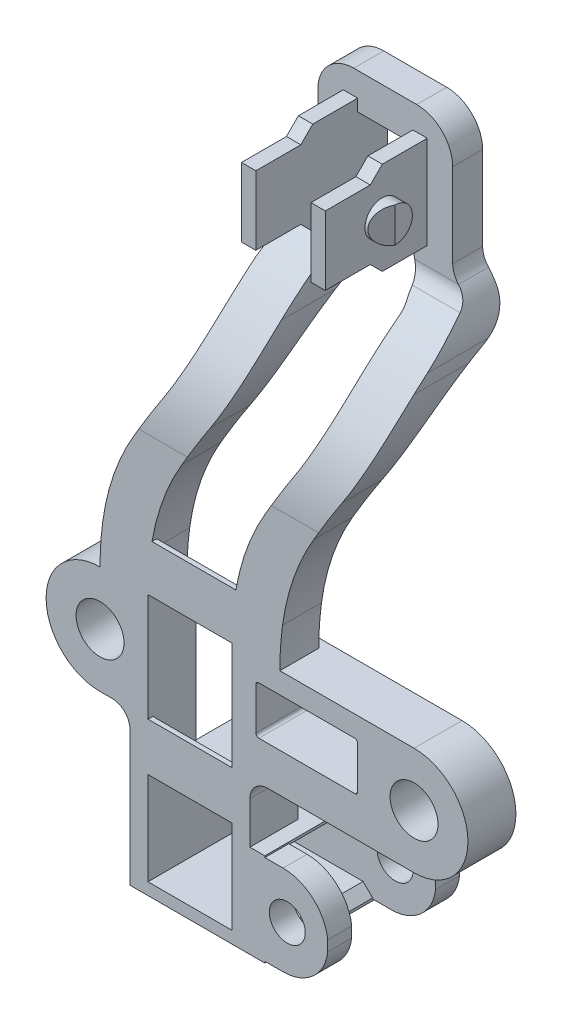
SolidWorks part; units mm, degrees
material "PET"
ref_plane "Front Plane" through (0, 0, 0) normal (0, 0, 1) x (1, 0, 0)
ref_plane "Top Plane" through (0, 0, 0) normal (0, 1, 0) x (1, 0, 0)
ref_plane "Right Plane" through (0, 0, 0) normal (1, 0, 0) x (0, 0, -1)
sketch "Sketch1" plane through (0, 0, 0) normal (0, 0, 1) x (1, 0, 0)
  line L0 (42.5, -2.5) -> (26.5, -2.5)
  line L1 (43, -2) -> (43, 5)
  line L2 (42.5, 5.5) -> (26.5, 5.5)
  line L3 (26, -2) -> (26, 5)
  line L84 (38, -34.5) -> (38, -19)
  line L94 (19.35, 79.25) -> (19.35, 65.25)
  line L96 (41.85, 79.25) -> (41.85, 65.25)
  line L97 (25.35, 85.25) -> (35.85, 85.25)
  line L112 (30, 9) -> (52.4, 9)
  line L113 (39.9183, 37.9809) -> (35.6739, 30.809)
  line L114 (31.9183, 37.7984) -> (27.6739, 30.6266)
  line L115 (17.9183, 37.7984) -> (13.6739, 30.6266)
  line L116 (9.9183, 37.9809) -> (5.6739, 30.809)
  line L121 (22, -19) -> (8, -19)
  line L122 (8, -19) -> (8, 8.8176)
  line L123 (22, -19) -> (22, 8.8176)
  line L126 (52.4, -9) -> (28, -9)
  line L127 (25, -12) -> (25, -19)
  line L128 (25, -19) -> (38, -19)
  line L129 (0, -9) -> (2, -9)
  line L130 (5, -12) -> (5, -34.5)
  line L131 (5, -34.5) -> (38, -34.5)
  line L134 (26, 65.25) -> (26, 79.25)
  line L135 (26, 79.25) -> (35.2, 79.25)
  line L136 (35.2, 65.25) -> (35.2, 79.25)
  circle A66 centre (0, 0) radius 4
  circle A67 centre (52.4, 0) radius 4
  arc A68 (43, 5) -> (42.5, 5.5) centre (42.5, 5) ccw
  arc A69 (42.5, -2.5) -> (43, -2) centre (42.5, -2) ccw
  arc A70 (26.5, -2.5) -> (26, -2) centre (26.5, -2) cw
  arc A71 (26.5, 5.5) -> (26, 5) centre (26.5, 5) ccw
  arc A73 (52.4, -9) -> (52.4, 9) centre (52.4, 0) ccw
  arc A122 (25.35, 85.25) -> (19.35, 79.25) centre (25.35, 79.25) ccw
  arc A123 (41.85, 79.25) -> (35.85, 85.25) centre (35.85, 79.25) ccw
  arc A134 (0, 9) -> (0, -9) centre (0, 0) ccw
  arc A142 (30.4608, 15.8181) -> (30, 9) centre (80.6766, 9) ccw
  arc A146 (30.4608, 15.8181) -> (35.6739, 30.809) centre (70.0971, 10.4364) cw
  arc A147 (45.1088, 52.8075) -> (39.9183, 37.9809) centre (5.4951, 58.3534) cw
  arc A148 (22.4608, 15.6357) -> (22, 8.8176) centre (72.6766, 8.8176) ccw
  arc A149 (37.1088, 52.6251) -> (37.5686, 57.8889) centre (-13.259, 59.6766) ccw
  arc A150 (22.4608, 15.6357) -> (27.6739, 30.6266) centre (62.0971, 10.254) cw
  arc A151 (37.1088, 52.6251) -> (31.9183, 37.7984) centre (-2.5049, 58.171) cw
  arc A152 (8.4608, 15.6357) -> (8, 8.8176) centre (58.6766, 8.8176) ccw
  arc A153 (23.1088, 52.6251) -> (23.5705, 57.9444) centre (-27.259, 59.6766) ccw
  arc A154 (8.4608, 15.6357) -> (13.6739, 30.6266) centre (48.0971, 10.254) cw
  arc A155 (23.1088, 52.6251) -> (17.9183, 37.7984) centre (-16.5049, 58.171) cw
  arc A156 (0.4608, 15.8181) -> (0, 9) centre (50.6766, 9) ccw
  arc A158 (0.4608, 15.8181) -> (5.6739, 30.809) centre (40.0971, 10.4364) cw
  arc A159 (15.1088, 52.8075) -> (9.9183, 37.9809) centre (-24.5049, 58.3534) cw
  arc A160 (15.1088, 52.8075) -> (15.4789, 56.3512) centre (-35.259, 59.859) ccw
  arc A161 (18.2877, 62.6349) -> (19.35, 65.25) centre (15.6, 65.25) ccw
  arc A162 (45.1088, 52.8075) -> (45.3737, 55.0669) centre (-5.259, 59.859) ccw
  arc A163 (41.85, 65.25) -> (42.8232, 62.7298) centre (45.6, 65.25) ccw
  arc A164 (45.3737, 55.0669) -> (42.8232, 62.7298) centre (35.4182, 56.0091) ccw
  arc A165 (18.2877, 62.6349) -> (15.4789, 56.3512) centre (25.4551, 55.6615) ccw
  arc A169 (35.2, 65.25) -> (37.1876, 59.1352) centre (45.6, 65.25) ccw
  arc A170 (23.9614, 59.0655) -> (26, 65.25) centre (15.6, 65.25) ccw
  arc A171 (37.1876, 59.1352) -> (37.5686, 57.8889) centre (35.5698, 57.9592) cw
  arc A172 (23.9614, 59.0655) -> (23.5705, 57.9444) centre (25.5693, 57.8762) ccw
  arc A173 (2, -9) -> (5, -12) centre (2, -12) cw
  arc A174 (28, -9) -> (25, -12) centre (28, -12) ccw
extrude "Boss-Extrude1" add sketch "Sketch1" along normal blind 22
sketch "Sketch4" plane through (41.85, 0, 0) normal (1, 0, 0) x (0, 0, -1)
  line L1 (-22, 81.25) -> (-5, 81.25)
  line L2 (-22, 81.25) -> (-22, 65.75)
  line L3 (-22, 65.75) -> (-5, 65.75)
  line L4 (-5, 81.25) -> (-5, 65.75)
  circle A0 centre (-12.5, 73.5) radius 2.9
sketch "Sketch5" plane through (19.35, 0, 0) normal (-1, 0, 0) x (0, 0, 1)
  line L3 (5, 81.25) -> (5, 65.75)
  line L4 (22, 65.75) -> (5, 65.75)
  line L5 (22, 81.25) -> (22, 65.75)
  line L6 (22, 81.25) -> (5, 81.25)
  circle A1 centre (12.5, 73.5) radius 2.9
extrude "Cut-Extrude2" cut sketch "Sketch5" against normal offset from surface (4.25 mm away) 2.4 up to face at (26, 72.25, 11)
extrude "Cut-Extrude3" cut sketch "Sketch4" against normal offset from surface (4.25 mm away) 2.4 up to face at (35.2, 72.25, 11)
sketch "Sketch6" plane through (23.6, 0, 0) normal (-1, 0, 0) x (0, 0, 1)
  line L7 (12.5, 81.25) -> (14.5, 79.25)
  line L8 (14.5, 79.25) -> (22, 79.25)
  line L10 (12.5, 65.75) -> (14.5, 67.75)
  line L11 (14.5, 67.75) -> (22, 67.75)
  line L12 (12.5, 81.25) -> (22, 81.25)
  line L13 (22, 81.25) -> (22, 79.25)
  line L14 (12.5, 65.75) -> (22, 65.75)
  line L15 (22, 65.75) -> (22, 67.75)
extrude "Cut-Extrude4" cut sketch "Sketch6" against normal up to surface (14 mm away)
sketch "Sketch7" plane through (0, 0, 22) normal (0, 0, 1) x (1, 0, 0)
  line L5 (19.35, 65.75) -> (19.35, 65.25)
  line L7 (19.35, 65.25) -> (41.85, 65.25)
  line L8 (19.35, 85.25) -> (41.85, 85.25)
  line L9 (41.85, 65.25) -> (41.85, 65.75)
  line L11 (19.35, 85.25) -> (19.35, 81.25)
  line L16 (41.85, 85.25) -> (41.85, 81.25)
  line L19 (26, 65.75) -> (26, 81.25)
  line L21 (35.2, 65.75) -> (35.2, 81.25)
  line L22 (19.35, 65.75) -> (26, 65.75)
  line L23 (41.85, 65.75) -> (35.2, 65.75)
  line L24 (19.35, 81.25) -> (26, 81.25)
  line L25 (41.85, 81.25) -> (35.2, 81.25)
extrude "Cut-Extrude5" cut sketch "Sketch7" against normal up to surface (17 mm away) up to face at (40.0984, 74.6529, 5)
sketch "Sketch8" plane through (0, 81.25, 0) normal (0, 1, 0) x (1, 0, 0)
  line L0 (21.5, -12.5) -> (23.1, -15.4)
  line L3 (21.475, -9.6) -> (21.5, -12.5)
  line L4 (37.6, -15.4) -> (41.85, -15.4) construction
  line L6 (23.6, -9.6) -> (19.35, -9.6) construction
  line L15 (39.7, -12.5) -> (38.1, -15.4)
  line L16 (19.35, -9.6) -> (21.475, -9.6)
  line L17 (19.35, -9.6) -> (19.35, -15.4)
  line L18 (19.35, -15.4) -> (23.1, -15.4)
  line L19 (39.725, -9.6) -> (39.7, -12.5)
  line L20 (41.85, -9.6) -> (37.6, -9.6) construction
  line L21 (41.85, -9.6) -> (39.725, -9.6)
  line L24 (38.1, -15.4) -> (41.85, -15.4)
  line L25 (41.85, -15.4) -> (41.85, -9.6)
extrude "Cut-Extrude6" cut sketch "Sketch8" against normal up to surface (15.5 mm away) up to face at (36.4, 65.75, 8.75)
sketch "Sketch12" plane through (0, 0, 0) normal (1, 0, 0) x (0, 0, -1)
  line L2 (-22, 65.25) -> (-5, 65.25)
  line L4 (-15.5, 9) -> (0, 9)
  line L7 (-5, 65.25) -> (-5, 62.7396)
  line L9 (-15.5, 32.1618) -> (-15.5, 9)
  line L11 (-22, 65.25) -> (-22, 32.1618)
  line L12 (0, 9) -> (0, 60.9585)
  arc A4 (-3.5942, 54.281) -> (-15.5, 32.1618) centre (11, 32.1618) ccw
  arc A5 (-6.4167, 60.1914) -> (-22, 32.1618) centre (11, 32.1618) ccw
  arc A6 (-6.4167, 60.1914) -> (-5, 62.7396) centre (-8, 62.7396) ccw
  arc A7 (-3.5942, 54.281) -> (0, 60.9585) centre (-8, 60.9585) ccw
extrude "Cut-Extrude7" cut sketch "Sketch12" against normal through all both and the other way through all
sketch "Sketch13" plane through (0, 0, 0) normal (1, 0, 0) x (0, 0, -1)
  line L2 (-14, 9) -> (0, 9)
  line L10 (0, 9) -> (0, -19)
  line L11 (-14, -19) -> (0, -19)
  line L12 (-14, 9) -> (-14, -19)
extrude "Cut-Extrude8" cut sketch "Sketch13" against normal through all both and the other way through all
sketch "Sketch14" plane through (38, 0, 0) normal (1, 0, 0) x (0, 0, -1)
  line L0 (-18, -21) -> (-4, -21)
  line L1 (-18, -21) -> (-18, -32.5)
  line L2 (-18, -32.5) -> (-4, -32.5)
  line L3 (-4, -21) -> (-4, -32.5)
extrude "Cut-Extrude9" cut sketch "Sketch14" against normal up to surface (30 mm away) up to face at (8, -5.0912, 18)
sketch "Sketch15" plane through (0, 0, 22) normal (0, 0, 1) x (1, 0, 0)
  line L3 (8, -32.5) -> (22, -32.5)
  line L4 (8, -32.5) -> (8, -19)
  line L5 (8, -19) -> (22, -19)
  line L6 (22, -32.5) -> (22, -19)
extrude "Cut-Extrude10" cut sketch "Sketch15" against normal up to surface (8 mm away) up to face at (34.5, 1.5, 14)
sketch "Sketch16" plane through (0, 0, 0) normal (0, 0, -1) x (-1, 0, 0)
  line L4 (-30.55, -19.25) -> (-38, -19.25)
  line L5 (-30.55, -34.25) -> (-38, -34.25)
  line L6 (-38, -34.25) -> (-38, -27.6146)
  line L7 (-38, -25.8854) -> (-38, -19.25)
  arc A3 (-30.55, -19.25) -> (-38, -25.8854) centre (-30.55, -26.75) ccw
  circle A4 centre (-31.25, -26.75) radius 3
  arc A5 (-38, -27.6146) -> (-30.55, -34.25) centre (-30.55, -26.75) ccw
extrude "Cut-Extrude11" cut sketch "Sketch16" against normal up to surface (22 mm away) up to face at (36.4, 73.5, 22)
sketch "Sketch17" plane through (38, 0, 0) normal (1, 0, 0) x (0, 0, -1)
  line L0 (-18, -34.25) -> (-18, -19.25)
  line L1 (-4, -19.25) -> (-4, -34.25)
  line L12 (-4, -34.25) -> (0, -34.25)
  line L13 (-4, -19.25) -> (0, -19.25)
  line L14 (-22, -19) -> (0, -19)
  line L15 (-22, -19) -> (-22, -19.25)
  line L16 (-22, -19.25) -> (-18, -19.25)
  line L17 (0, -19) -> (0, -19.25)
  line L18 (-22, -34.25) -> (-18, -34.25)
  line L19 (-22, -34.25) -> (-22, -34.5)
  line L20 (-22, -34.5) -> (0, -34.5)
  line L21 (0, -34.25) -> (0, -34.5)
extrude "Cut-Extrude12" cut sketch "Sketch17" against normal blind 10.5
chamfer "Chamfer1" distance 1.6 angle 45 2 edges at (27.5, -21, 11) (27.5, -32.5, 11)
sketch "Sketch18" plane through (0, 0, 22) normal (0, 0, 1) x (1, 0, 0)
  line L11 (8, -9) -> (22, -9)
  line L12 (8, -17) -> (22, -17)
  line L13 (22, -9) -> (22, -17)
  line L14 (8, -9) -> (8, -17)
  line L16 (8.0003, 9) -> (22.0003, 9)
  line L18 (8.67, 17) -> (22.67, 17)
  arc A1 (8.4608, 15.6357) -> (8.0003, 9) centre (58.6766, 8.8176) ccw
  arc A2 (22.4608, 15.6357) -> (22.0003, 9) centre (72.6766, 8.8176) ccw
  arc A6 (8.67, 17) -> (8.4608, 15.6357) centre (48.0971, 10.254) ccw
  arc A7 (22.67, 17) -> (22.4608, 15.6357) centre (62.0971, 10.254) ccw
extrude "Boss-Extrude2" add sketch "Sketch18" against normal blind 0.8
